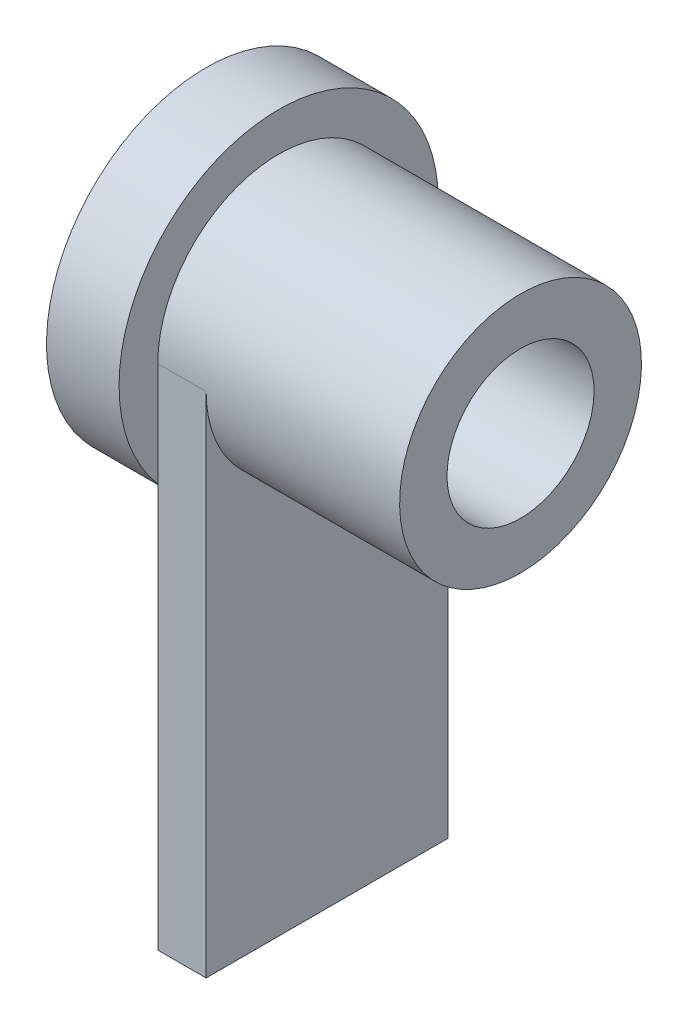
SolidWorks part; units mm, degrees
material "6061 Alloy"
ref_plane "Front Plane" through (0, 0, 0) normal (0, 0, 1) x (1, 0, 0)
ref_plane "Top Plane" through (0, 0, 0) normal (0, 1, 0) x (1, 0, 0)
ref_plane "Right Plane" through (0, 0, 0) normal (1, 0, 0) x (0, 0, -1)
sketch "Sketch1" plane through (0, 0, 0) normal (0, 0, 1) x (1, 0, 0)
  line L0 (0, 0) -> (0, -66.675)
  line L1 (0, -66.675) -> (6.35, -66.675)
  line L2 (6.35, -66.675) -> (6.35, 0)
  line L3 (6.35, 0) -> (0, 0)
  dimension "D1" = 6.35
  dimension "D2" = 66.675
extrude "Boss-Extrude1" add sketch "Sketch1" along normal mid plane 31.75
sketch "Sketch2" plane through (0, 0, 0) normal (-1, 0, 0) x (0, 0, 1)
  circle A0 centre (0, 0) radius 15.875
extrude "Boss-Extrude2" add sketch "Sketch2" against normal blind 31.75
sketch "Sketch3" plane through (0, 0, 0) normal (-1, 0, 0) x (0, 0, 1)
  circle A0 centre (0, 0) radius 20.955
  dimension "D1" = 41.91
extrude "Boss-Extrude3" add sketch "Sketch3" along normal blind 9.525
sketch "Sketch4" plane through (0, 0, 0) normal (0, 0, 1) x (1, 0, 0)
  line L0 (-9.525, 19.1135) -> (-6.35, 19.1135)
  line L1 (-9.525, 20.955) -> (-9.525, -20.955) construction
  line L2 (-6.35, 19.1135) -> (-6.35, 9.652)
  line L3 (-6.35, 9.652) -> (31.75, 9.652)
  line L4 (31.75, -15.875) -> (31.75, 15.875) construction
  line L5 (31.75, 9.652) -> (31.75, 0)
  line L6 (31.75, 0) -> (-9.525, 0)
  line L7 (-9.525, 0) -> (-9.525, 19.1135)
  dimension "D1" = 9.652
  dimension "D2" = 19.1135
  dimension "D3" = 3.175
revolve "Cut-Revolve1" cut sketch "Sketch4" angle 360 about L6
